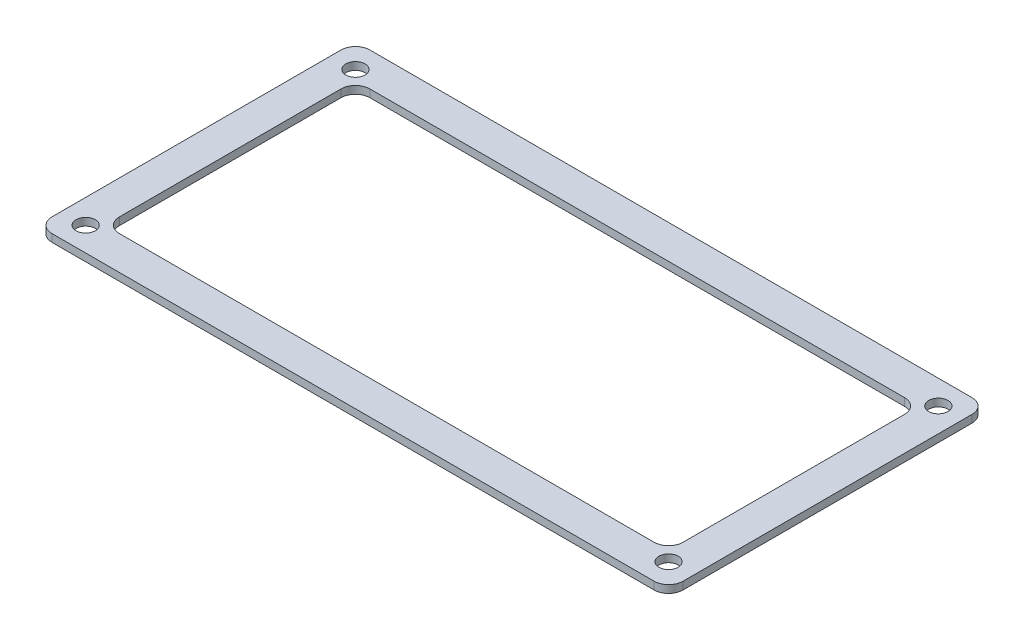
SolidWorks part; units mm, degrees
material "Silicon Rubber"
ref_plane "Front Plane" through (0, 0, 0) normal (0, 0, 1) x (1, 0, 0)
ref_plane "Top Plane" through (0, 0, 0) normal (0, 1, 0) x (1, 0, 0)
ref_plane "Right Plane" through (0, 0, 0) normal (1, 0, 0) x (0, 0, -1)
sketch "Sketch1" plane through (0, 0, 0) normal (0, 1, 0) x (1, 0, 0)
  line L0 (-55, 0) -> (55, 0) construction
  line L1 (-65.5, 33) -> (65.5, 33)
  line L2 (-65.5, 33) -> (-65.5, -33)
  line L3 (-65.5, -33) -> (65.5, -33)
  line L4 (65.5, 33) -> (65.5, -33)
  line L5 (0, -55) -> (0, 55) construction
  point P4 (-65.5, 0)
  point P7 (0, 33)
  dimension "D1" = 66
  dimension "D2" = 131
extrude "Boss-Extrude1" add sketch "Sketch1" along normal blind 1.5875
sketch "Sketch2" plane through (0, 1.5875, 0) normal (0, 1, 0) x (1, 0, 0)
  line L0 (-65.5, -33) -> (65.5, -33) construction
  line L1 (-58.5, -26) -> (-6, -26)
  line L2 (-58.5, -26) -> (-58.5, 26)
  line L3 (-58.5, 26) -> (-6, 26)
  line L4 (-6, -26) -> (-6, 26)
  line L5 (1, -26) -> (40.5, -26)
  line L6 (1, -26) -> (1, 26)
  line L7 (1, 26) -> (40.5, 26)
  line L8 (40.5, -26) -> (40.5, 26)
  line L9 (-65.5, 33) -> (-65.5, -33) construction
  line L10 (65.5, 33) -> (-65.5, 33) construction
  dimension "D1" = 7
  dimension "D2" = 7
  dimension "D3" = 7
  dimension "D4" = 52.5
  dimension "D5" = 7
  dimension "D6" = 39.5
extrude "Cut-Extrude1" [suppressed] cut sketch "Sketch2" against normal through all
sketch "Sketch3" plane through (0, 1.5875, 0) normal (0, 1, 0) x (1, 0, 0)
  line L0 (-65.5, -33) -> (65.5, -33) construction
  line L1 (-58.5, -26) -> (58.5, -26)
  line L2 (-58.5, -26) -> (-58.5, 26)
  line L3 (-58.5, 26) -> (58.5, 26)
  line L4 (58.5, -26) -> (58.5, 26)
  line L5 (65.5, 33) -> (-65.5, 33) construction
  line L6 (65.5, -33) -> (65.5, 33) construction
  line L7 (-65.5, 33) -> (-65.5, -33) construction
  dimension "D1" = 7
  dimension "D2" = 7
  dimension "D3" = 7
  dimension "D4" = 7
extrude "Cut-Extrude2" cut sketch "Sketch3" against normal through all
sketch "Sketch4" plane through (0, 1.5875, 0) normal (0, 1, 0) x (1, 0, 0)
  line L0 (-65.5, 33) -> (-65.5, -33) construction
  line L1 (65.5, -33) -> (65.5, 33) construction
  line L2 (-65.5, -33) -> (65.5, -33) construction
  line L3 (65.5, 33) -> (-65.5, 33) construction
  circle A0 centre (-60.5, 28) radius 2
  circle A1 centre (60.5, 28) radius 2
  circle A2 centre (60.5, -28) radius 2
  circle A3 centre (-60.5, -28) radius 2
  dimension "D1" = 4
  dimension "D2" = 5
  dimension "D3" = 5
  dimension "D4" = 5
  dimension "D5" = 5
extrude "Cut-Extrude3" cut sketch "Sketch4" against normal through all
fillet "Fillet1" radius 3 8 edges at (65.5, 0.7937, 33) (65.5, 0.7937, -33) (-65.5, 0.7937, -33) (-65.5, 0.7937, 33) (58.5, 0.7937, 26) (-58.5, 0.7937, 26) (58.5, 0.7937, -26) (-58.5, 0.7937, -26)
